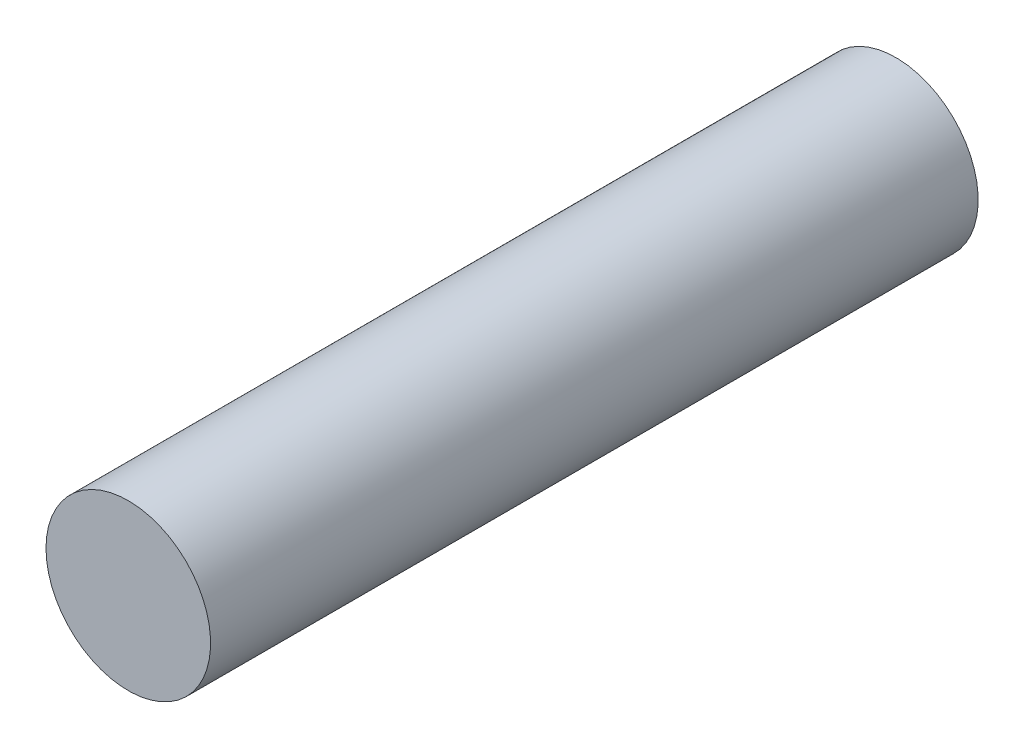
SolidWorks part; units mm, degrees
ref_plane "Front Plane" through (0, 0, 0) normal (0, 0, 1) x (1, 0, 0)
ref_plane "Top Plane" through (0, 0, 0) normal (0, 1, 0) x (1, 0, 0)
ref_plane "Right Plane" through (0, 0, 0) normal (1, 0, 0) x (0, 0, -1)
sketch "Sketch1" plane through (0, 0, 0) normal (0, 0, 1) x (1, 0, 0)
  circle A0 centre (0, 0) radius 9.65
  dimension "D1" = 19.3
extrude "Boss-Extrude1" add sketch "Sketch1" along normal blind 90
scale "Scale1" scale about centroid uniform scaling yes scale factor 1.5
